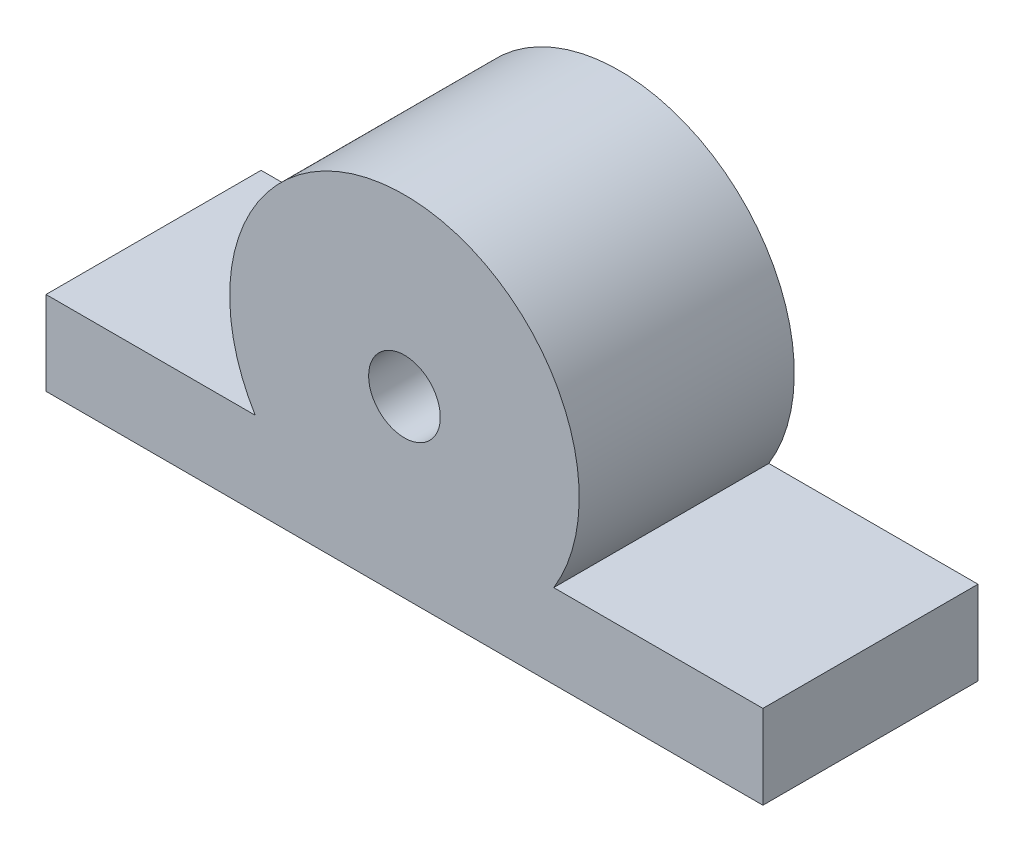
SolidWorks part; units mm, degrees
ref_plane "Front Plane" through (0, 0, 0) normal (0, 0, 1) x (1, 0, 0)
ref_plane "Top Plane" through (0, 0, 0) normal (0, 1, 0) x (1, 0, 0)
ref_plane "Right Plane" through (0, 0, 0) normal (1, 0, 0) x (0, 0, -1)
sketch "Sketch2" plane through (0, 0, 0) normal (0, 0, 1) x (1, 0, 0)
  line L0 (0, -30.9562) -> (-79.6247, -30.9562) construction
  line L1 (26.4431, -16.0951) -> (63.5, -16.0951)
  line L2 (-63.5, -30.9563) -> (63.5, -30.9563)
  line L3 (-63.5, -30.9563) -> (-63.5, -16.0951)
  line L4 (-63.5, -16.0951) -> (-26.4431, -16.0951)
  line L5 (63.5, -30.9563) -> (63.5, -16.0951)
  circle A0 centre (0, 0) radius 6.35
  arc A1 (26.4431, -16.0951) -> (-26.4431, -16.0951) centre (0, 0) ccw
  dimension "D1" = 12.7
  dimension "D2" = 61.9125
  dimension "D3" = 127
  dimension "D4" = 63.5
extrude "Boss-Extrude1" add sketch "Sketch2" along normal blind 38.1
